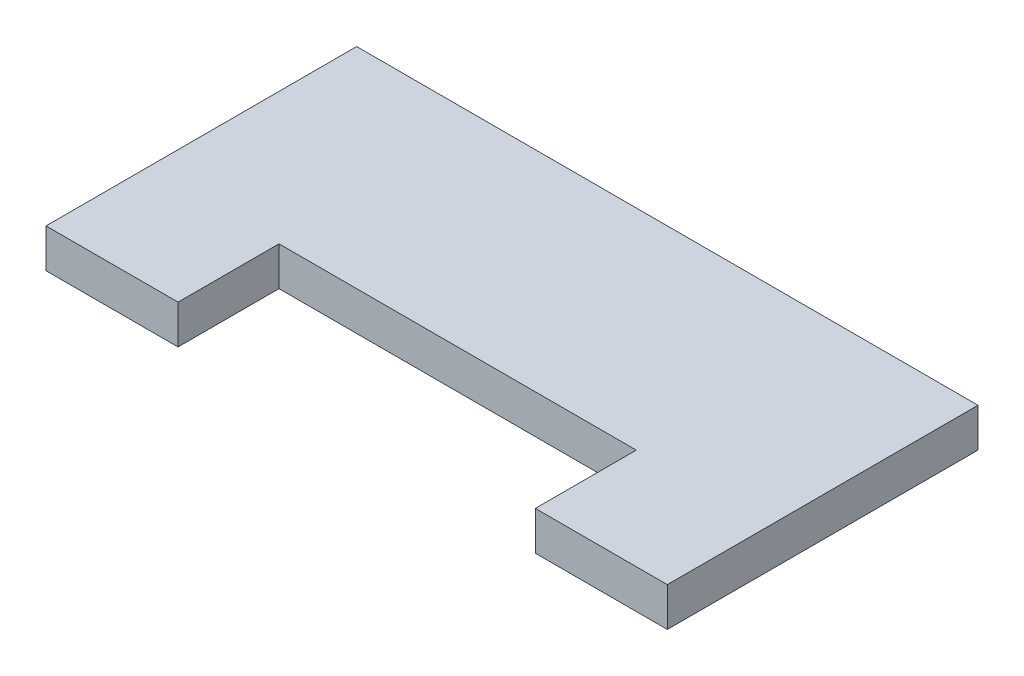
SolidWorks part; units mm, degrees
material "Copper"
ref_plane "Front Plane" through (0, 0, 0) normal (0, 0, 1) x (1, 0, 0)
ref_plane "Top Plane" through (0, 0, 0) normal (0, 1, 0) x (1, 0, 0)
ref_plane "Right Plane" through (0, 0, 0) normal (1, 0, 0) x (0, 0, -1)
sketch "Sketch1" plane through (0, 0, 0) normal (0, 1, 0) x (1, 0, 0)
  line L1 (0, 0) -> (-80, 0)
  line L2 (0, 0) -> (0, 40)
  line L3 (0, 40) -> (-80, 40)
  line L4 (-80, 0) -> (-80, 40)
  line L5 (-63, 0) -> (-17, 0)
  line L6 (-63, 0) -> (-63, 13)
  line L7 (-63, 13) -> (-17, 13)
  line L8 (-17, 0) -> (-17, 13)
  point P9 (-40, 13)
  point P10 (-40, 40)
  dimension "D1" = 13
  dimension "D2" = 40
  dimension "D3" = 0
  dimension "D4" = 46
  dimension "D5" = 80
extrude "Boss-Extrude1" add sketch "Sketch1" along normal blind 5 contours L8 L1 L2 L3 L4 L6 L7
